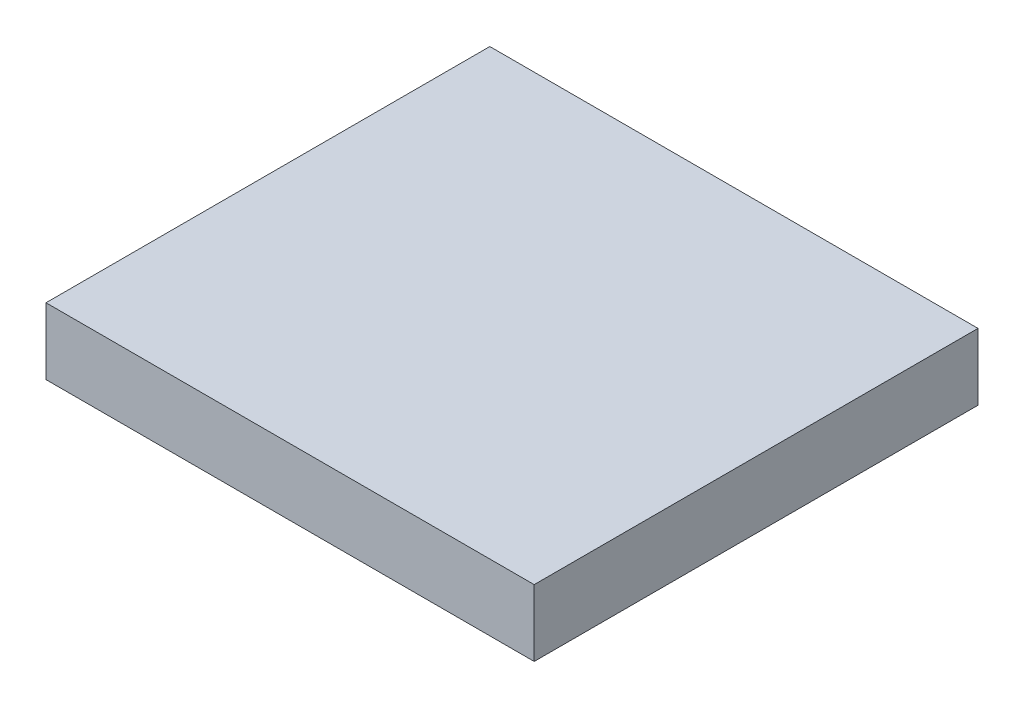
SolidWorks part; units mm, degrees
ref_plane "Front Plane" through (0, 0, 0) normal (0, 0, 1) x (1, 0, 0)
ref_plane "Top Plane" through (0, 0, 0) normal (0, 1, 0) x (1, 0, 0)
ref_plane "Right Plane" through (0, 0, 0) normal (1, 0, 0) x (0, 0, -1)
sketch "Sketch1" plane through (0, 0, 0) normal (0, 1, 0) x (1, 0, 0)
  line L4 (-35, 20) -> (-35, -20)
  line L25 (-79, 20) -> (-79, -20)
  line L29 (-35, 20) -> (-79, 20)
  line L30 (-35, -20) -> (-79, -20)
  point P0 (0, 0)
  dimension "D1" = 44
  dimension "D2" = 40
extrude "Boss-Extrude1" add sketch "Sketch1" against normal blind 6
